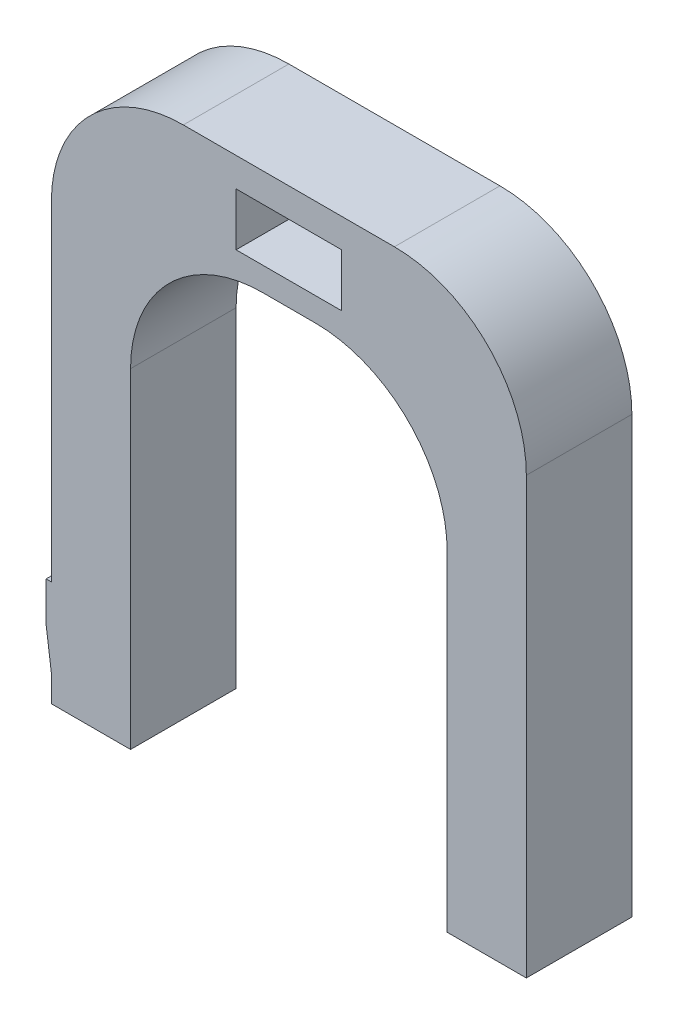
SolidWorks part; units mm, degrees
ref_plane "正面" through (0, 0, 0) normal (0, 0, 1) x (1, 0, 0)
ref_plane "平面" through (0, 0, 0) normal (0, 1, 0) x (1, 0, 0)
ref_plane "右側面" through (0, 0, 0) normal (1, 0, 0) x (0, 0, -1)
sketch "ｽｹｯﾁ2" plane through (0, 0, 0) normal (0, 0, 1) x (1, 0, 0)
  line L1 (0, 0) -> (18, 0)
  line L2 (0, 0) -> (0, 21.5)
  line L3 (0, 21.5) -> (18, 21.5)
  line L4 (18, 0) -> (18, 21.5)
  dimension "D1" = 21.5
  dimension "D2" = 18
extrude "ﾎﾞｽ - 押し出し1" add sketch "ｽｹｯﾁ2" along normal blind 4
sketch "ｽｹｯﾁ3" plane through (0, 0, 4) normal (0, 0, 1) x (1, 0, 0)
  line L0 (0, 0) -> (18, 0) construction
  line L1 (3, 0) -> (15, 0)
  line L2 (3, 0) -> (3, 17.5)
  line L3 (3, 17.5) -> (15, 17.5)
  line L4 (15, 0) -> (15, 17.5)
  line L5 (0, 21.5) -> (0, 0) construction
  line L6 (18, 0) -> (18, 21.5) construction
  line L7 (18, 21.5) -> (0, 21.5) construction
  dimension "D1" = 3
  dimension "D2" = 3
  dimension "D3" = 4
extrude "ｶｯﾄ - 押し出し1" cut sketch "ｽｹｯﾁ3" against normal through all
fillet "ﾌｨﾚｯﾄ1" radius 5 2 edges at (15, 17.5, 2) (3, 17.5, 2)
fillet "ﾌｨﾚｯﾄ2" radius 5 2 edges at (18, 21.5, 2) (0, 21.5, 2)
sketch "ｽｹｯﾁ4" plane through (0, 0, 4) normal (0, 0, 1) x (1, 0, 0)
  line L0 (0, 16.5) -> (0, 0) construction
  line L1 (7, 20.4009) -> (11, 20.4009)
  line L2 (7, 20.4009) -> (7, 18.4009)
  line L3 (7, 18.4009) -> (11, 18.4009)
  line L4 (11, 20.4009) -> (11, 18.4009)
  dimension "D1" = 2
  dimension "D2" = 4
  dimension "D3" = 7
extrude "ｶｯﾄ - 押し出し2" cut sketch "ｽｹｯﾁ4" against normal through all
sketch "ｽｹｯﾁ5" plane through (0, 0, 0) normal (-1, 0, 0) x (0, 0, 1)
  line L0 (0, 16.5) -> (0, 0) construction
  line L1 (0, 1) -> (4, 1)
  line L2 (0, 1) -> (0, 4)
  line L3 (0, 4) -> (4, 4)
  line L4 (4, 1) -> (4, 4)
  line L5 (4, 16.5) -> (4, 0) construction
  line L6 (4, 0) -> (0, 0) construction
  dimension "D1" = 1
  dimension "D2" = 3
extrude "ﾎﾞｽ - 押し出し2" add sketch "ｽｹｯﾁ5" along normal blind 0.2
sketch "ｽｹｯﾁ6" plane through (0, 0, 4) normal (0, 0, 1) x (1, 0, 0)
  line L0 (0, 1) -> (-0.2, 2.5)
  line L1 (-0.2, 1) -> (-0.2, 4) construction
  line L2 (0, 1) -> (-0.2, 1)
  line L3 (-0.2, 1) -> (-0.2, 2.5)
extrude "ｶｯﾄ - 押し出し3" cut sketch "ｽｹｯﾁ6" against normal through all
